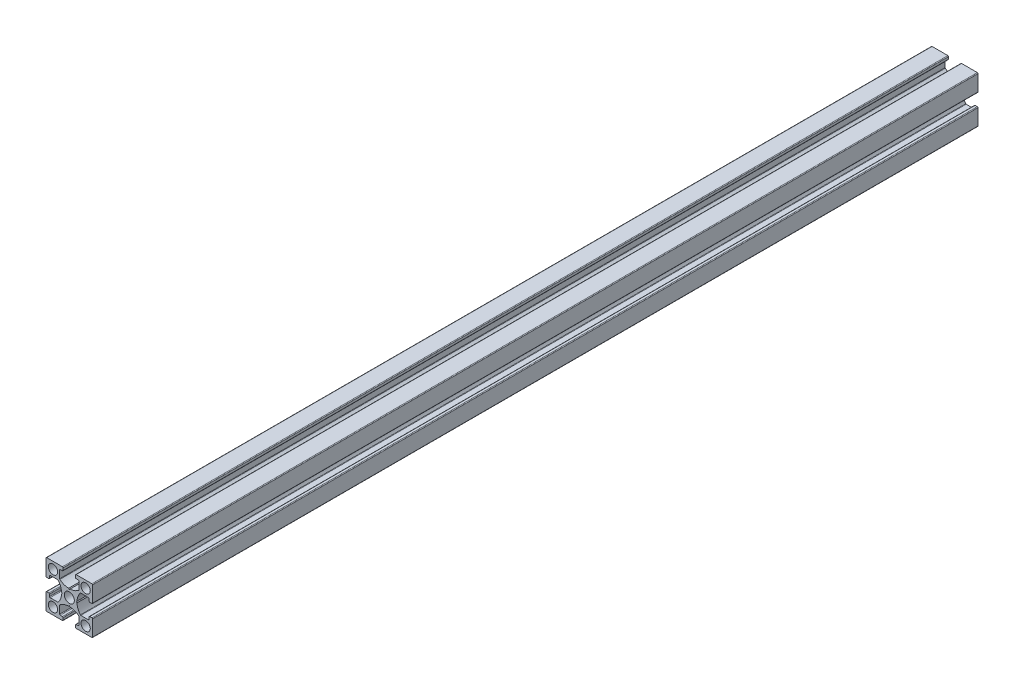
SolidWorks part; units mm, degrees
ref_plane "정면" through (0, 0, 0) normal (0, 0, 1) x (1, 0, 0)
ref_plane "윗면" through (0, 0, 0) normal (0, 1, 0) x (1, 0, 0)
ref_plane "우측면" through (0, 0, 0) normal (1, 0, 0) x (0, 0, -1)
sketch "Model" plane through (0, 0, 0) normal (0, 0, 1) x (1, 0, 0)
  line L0 (2292.4151, 1187.1915) -> (2314.8128, 1187.1915) construction
  line L1 (2307.7639, 1192.1343) -> (2307.7639, 1195.3915)
  line L2 (2307.4639, 1195.6915) -> (2306.5639, 1195.6915)
  line L3 (2306.2639, 1195.9915) -> (2306.2639, 1196.8915)
  line L4 (2306.5639, 1197.1915) -> (2313.3139, 1197.1915)
  line L5 (2313.6139, 1196.8915) -> (2313.6139, 1190.1415)
  line L6 (2313.3139, 1189.8415) -> (2312.4139, 1189.8415)
  line L7 (2312.1139, 1190.1415) -> (2312.1139, 1191.0415)
  line L8 (2311.8139, 1191.3415) -> (2308.5567, 1191.3415)
  line L9 (2306.9212, 1187.4988) -> (2306.6139, 1187.1915)
  line L10 (2306.6139, 1187.1915) -> (2306.9212, 1186.8843)
  line L11 (2308.5567, 1183.0415) -> (2311.8139, 1183.0415)
  line L12 (2312.1139, 1183.3415) -> (2312.1139, 1184.2415)
  line L13 (2312.4139, 1184.5415) -> (2313.3139, 1184.5415)
  line L14 (2313.6139, 1184.2415) -> (2313.6139, 1177.4915)
  line L15 (2313.3139, 1177.1915) -> (2306.5639, 1177.1915)
  line L16 (2306.2639, 1177.4915) -> (2306.2639, 1178.3915)
  line L17 (2306.5639, 1178.6915) -> (2307.4639, 1178.6915)
  line L18 (2307.7639, 1178.9915) -> (2307.7639, 1182.2488)
  line L19 (2303.9212, 1183.8843) -> (2303.6139, 1184.1915)
  line L20 (2303.6139, 1184.1915) -> (2303.3066, 1183.8843)
  line L21 (2299.4639, 1182.2488) -> (2299.4639, 1178.9915)
  line L22 (2299.7639, 1178.6915) -> (2300.6639, 1178.6915)
  line L23 (2300.9639, 1178.3915) -> (2300.9639, 1177.4915)
  line L24 (2300.6639, 1177.1915) -> (2293.9139, 1177.1915)
  line L25 (2293.6139, 1177.4915) -> (2293.6139, 1184.2415)
  line L26 (2293.9139, 1184.5415) -> (2294.8139, 1184.5415)
  line L27 (2295.1139, 1184.2415) -> (2295.1139, 1183.3415)
  line L28 (2295.4139, 1183.0415) -> (2298.6712, 1183.0415)
  line L29 (2300.3066, 1186.8843) -> (2300.6139, 1187.1915)
  line L30 (2300.6139, 1187.1915) -> (2300.3066, 1187.4988)
  line L31 (2298.6712, 1191.3415) -> (2295.4139, 1191.3415)
  line L32 (2295.1139, 1191.0415) -> (2295.1139, 1190.1415)
  line L33 (2294.8139, 1189.8415) -> (2293.9139, 1189.8415)
  line L34 (2293.6139, 1190.1415) -> (2293.6139, 1196.8915)
  line L35 (2293.9139, 1197.1915) -> (2300.6639, 1197.1915)
  line L36 (2300.9639, 1196.8915) -> (2300.9639, 1195.9915)
  line L37 (2300.6639, 1195.6915) -> (2299.7639, 1195.6915)
  line L38 (2299.4639, 1195.3915) -> (2299.4639, 1192.1343)
  line L39 (2303.3066, 1190.4988) -> (2303.6139, 1190.1915)
  line L40 (2303.6139, 1190.1915) -> (2303.9212, 1190.4988)
  line L41 (2294.1139, 1194.1915) -> (2299.1139, 1194.1915) construction
  line L42 (2296.6139, 1196.6915) -> (2296.6139, 1191.6915) construction
  line L43 (2294.1139, 1180.1915) -> (2299.1139, 1180.1915) construction
  line L44 (2296.6139, 1177.6915) -> (2296.6139, 1182.6915) construction
  line L45 (2303.6139, 1198.3904) -> (2303.6139, 1175.9927) construction
  line L46 (2313.1139, 1194.1915) -> (2308.1139, 1194.1915) construction
  line L47 (2310.6139, 1196.6915) -> (2310.6139, 1191.6915) construction
  line L48 (2310.6139, 1177.6915) -> (2310.6139, 1182.6915) construction
  line L49 (2313.1139, 1180.1915) -> (2308.1139, 1180.1915) construction
  circle A0 centre (2303.6139, 1187.1915) radius 2.15
  circle A1 centre (2296.6139, 1194.1915) radius 2
  circle A2 centre (2296.6139, 1180.1915) radius 2
  circle A3 centre (2310.6139, 1194.1915) radius 2
  circle A4 centre (2310.6139, 1180.1915) radius 2
  arc A5 (2307.7639, 1195.3915) -> (2307.4639, 1195.6915) centre (2307.4639, 1195.3915) ccw
  arc A6 (2306.2639, 1195.9915) -> (2306.5639, 1195.6915) centre (2306.5639, 1195.9915) ccw
  arc A7 (2306.5639, 1197.1915) -> (2306.2639, 1196.8915) centre (2306.5639, 1196.8915) ccw
  arc A8 (2313.6139, 1196.8915) -> (2313.3139, 1197.1915) centre (2313.3139, 1196.8915) ccw
  arc A9 (2313.3139, 1189.8415) -> (2313.6139, 1190.1415) centre (2313.3139, 1190.1415) ccw
  arc A10 (2312.1139, 1190.1415) -> (2312.4139, 1189.8415) centre (2312.4139, 1190.1415) ccw
  arc A11 (2312.1139, 1191.0415) -> (2311.8139, 1191.3415) centre (2311.8139, 1191.0415) ccw
  arc A12 (2308.5567, 1191.3415) -> (2308.3217, 1191.2281) centre (2308.5567, 1191.0415) ccw
  arc A13 (2308.3217, 1191.2281) -> (2306.9212, 1187.4988) centre (2313.4048, 1187.1915) ccw
  arc A14 (2306.9212, 1186.8843) -> (2308.3217, 1183.155) centre (2313.4048, 1187.1915) ccw
  arc A15 (2308.3217, 1183.155) -> (2308.5567, 1183.0415) centre (2308.5567, 1183.3415) ccw
  arc A16 (2311.8139, 1183.0415) -> (2312.1139, 1183.3415) centre (2311.8139, 1183.3415) ccw
  arc A17 (2312.4139, 1184.5415) -> (2312.1139, 1184.2415) centre (2312.4139, 1184.2415) ccw
  arc A18 (2313.6139, 1184.2415) -> (2313.3139, 1184.5415) centre (2313.3139, 1184.2415) ccw
  arc A19 (2313.3139, 1177.1915) -> (2313.6139, 1177.4915) centre (2313.3139, 1177.4915) ccw
  arc A20 (2306.2639, 1177.4915) -> (2306.5639, 1177.1915) centre (2306.5639, 1177.4915) ccw
  arc A21 (2306.5639, 1178.6915) -> (2306.2639, 1178.3915) centre (2306.5639, 1178.3915) ccw
  arc A22 (2307.4639, 1178.6915) -> (2307.7639, 1178.9915) centre (2307.4639, 1178.9915) ccw
  arc A23 (2307.7639, 1182.2488) -> (2307.6505, 1182.4837) centre (2307.4639, 1182.2488) ccw
  arc A24 (2307.6505, 1182.4837) -> (2303.9212, 1183.8843) centre (2303.6139, 1177.4007) ccw
  arc A25 (2303.3066, 1183.8843) -> (2299.5774, 1182.4837) centre (2303.6139, 1177.4007) ccw
  arc A26 (2299.5774, 1182.4837) -> (2299.4639, 1182.2488) centre (2299.7639, 1182.2488) ccw
  arc A27 (2299.4639, 1178.9915) -> (2299.7639, 1178.6915) centre (2299.7639, 1178.9915) ccw
  arc A28 (2300.9639, 1178.3915) -> (2300.6639, 1178.6915) centre (2300.6639, 1178.3915) ccw
  arc A29 (2300.6639, 1177.1915) -> (2300.9639, 1177.4915) centre (2300.6639, 1177.4915) ccw
  arc A30 (2293.6139, 1177.4915) -> (2293.9139, 1177.1915) centre (2293.9139, 1177.4915) ccw
  arc A31 (2293.9139, 1184.5415) -> (2293.6139, 1184.2415) centre (2293.9139, 1184.2415) ccw
  arc A32 (2295.1139, 1184.2415) -> (2294.8139, 1184.5415) centre (2294.8139, 1184.2415) ccw
  arc A33 (2295.1139, 1183.3415) -> (2295.4139, 1183.0415) centre (2295.4139, 1183.3415) ccw
  arc A34 (2298.6712, 1183.0415) -> (2298.9061, 1183.155) centre (2298.6712, 1183.3415) ccw
  arc A35 (2298.9061, 1183.155) -> (2300.3066, 1186.8843) centre (2293.8231, 1187.1915) ccw
  arc A36 (2300.3066, 1187.4988) -> (2298.9061, 1191.2281) centre (2293.8231, 1187.1915) ccw
  arc A37 (2298.9061, 1191.2281) -> (2298.6712, 1191.3415) centre (2298.6712, 1191.0415) ccw
  arc A38 (2295.4139, 1191.3415) -> (2295.1139, 1191.0415) centre (2295.4139, 1191.0415) ccw
  arc A39 (2294.8139, 1189.8415) -> (2295.1139, 1190.1415) centre (2294.8139, 1190.1415) ccw
  arc A40 (2293.6139, 1190.1415) -> (2293.9139, 1189.8415) centre (2293.9139, 1190.1415) ccw
  arc A41 (2293.9139, 1197.1915) -> (2293.6139, 1196.8915) centre (2293.9139, 1196.8915) ccw
  arc A42 (2300.9639, 1196.8915) -> (2300.6639, 1197.1915) centre (2300.6639, 1196.8915) ccw
  arc A43 (2300.6639, 1195.6915) -> (2300.9639, 1195.9915) centre (2300.6639, 1195.9915) ccw
  arc A44 (2299.7639, 1195.6915) -> (2299.4639, 1195.3915) centre (2299.7639, 1195.3915) ccw
  arc A45 (2299.4639, 1192.1343) -> (2299.5774, 1191.8994) centre (2299.7639, 1192.1343) ccw
  arc A46 (2299.5774, 1191.8994) -> (2303.3066, 1190.4988) centre (2303.6139, 1196.9824) ccw
  arc A47 (2303.9212, 1190.4988) -> (2307.6505, 1191.8994) centre (2303.6139, 1196.9824) ccw
  arc A48 (2307.6505, 1191.8994) -> (2307.7639, 1192.1343) centre (2307.4639, 1192.1343) ccw
extrude "보스-돌출1" add sketch "Model" along normal blind 380
